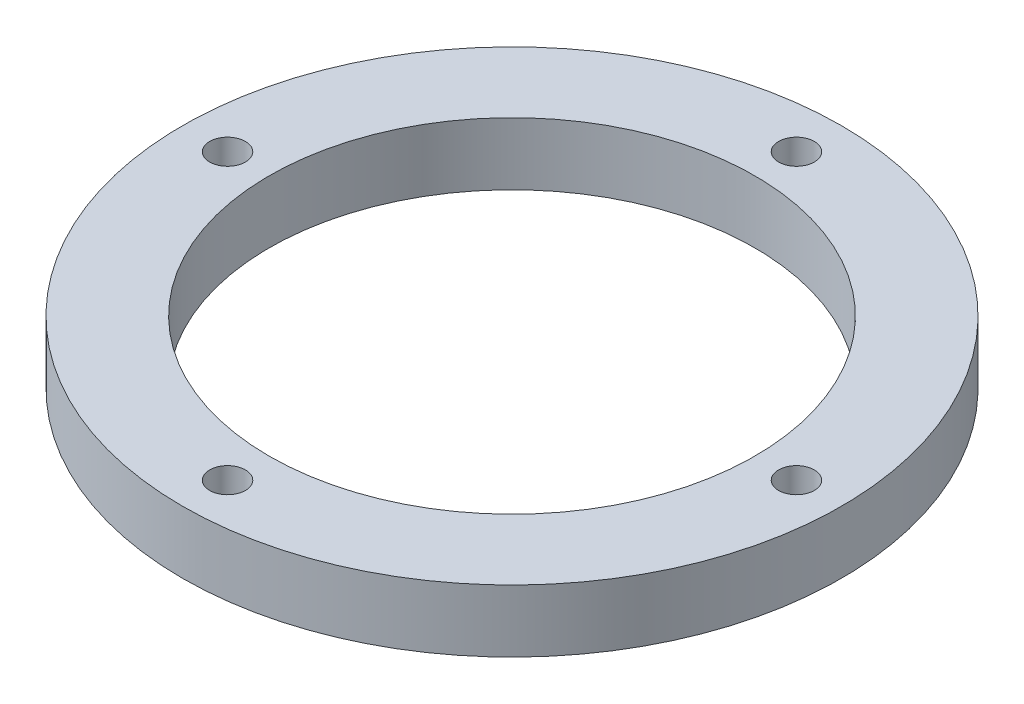
SolidWorks part; units mm, degrees
ref_plane "前视基准面" through (0, 0, 0) normal (0, 0, 1) x (1, 0, 0)
ref_plane "上视基准面" through (0, 0, 0) normal (0, 1, 0) x (1, 0, 0)
ref_plane "右视基准面" through (0, 0, 0) normal (1, 0, 0) x (0, 0, -1)
other "Configuration Table"
sketch "草图1" plane through (0, 0, 0) normal (0, 1, 0) x (1, 0, 0)
  circle A0 centre (0, 0) radius 47.5
  circle A1 centre (0, 0) radius 35
  dimension "D1" = 95
  dimension "D2" = 70
extrude "凸台-拉伸1" add sketch "草图1" along normal blind 9
sketch "草图2" plane through (0, 9, 0) normal (0, 1, 0) x (1, 0, 0)
  line L0 (0, 41) -> (0, 0) construction
  circle A0 centre (0, 41) radius 2.575
  circle A1 centre (41, 0) radius 2.575
  circle A2 centre (0, -41) radius 2.575
  circle A3 centre (-41, 0) radius 2.575
  point P13 (0, 0)
  dimension "D2" = 5.15
  dimension "D1" = 41
  dimension "D3" = 4
extrude "切除-拉伸1" cut sketch "草图2" against normal up to next
